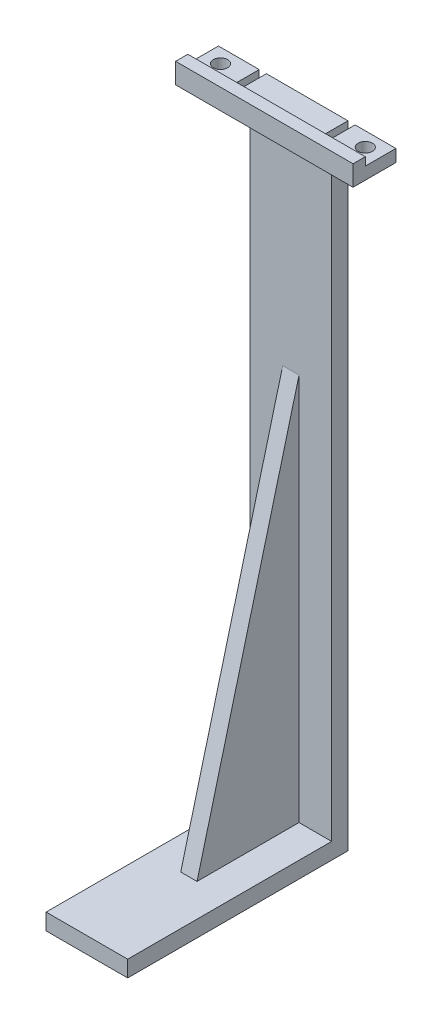
SolidWorks part; units mm, degrees
ref_plane "Front Plane" through (0, 0, 0) normal (0, 0, 1) x (1, 0, 0)
ref_plane "Top Plane" through (0, 0, 0) normal (0, 1, 0) x (1, 0, 0)
ref_plane "Right Plane" through (0, 0, 0) normal (1, 0, 0) x (0, 0, -1)
sketch "Sketch1" plane through (0, 0, 0) normal (0, 0, 1) x (1, 0, 0)
  line L1 (10, 77.5) -> (-10, 77.5)
  line L2 (10, 77.5) -> (10, -77.5)
  line L3 (10, -77.5) -> (-10, -77.5)
  line L4 (-10, 77.5) -> (-10, -77.5)
  line L5 (10, 77.5) -> (-10, -77.5) construction
  line L6 (10, -77.5) -> (-10, 77.5) construction
  point P0 (0, 0)
  dimension "D1" = 20
  dimension "D2" = 155
extrude "Boss-Extrude1" add sketch "Sketch1" along normal blind 4
sketch "Sketch2" plane through (0, 0, 4) normal (0, 0, 1) x (1, 0, 0)
  line L0 (10, -77.5) -> (10, 77.5) construction
  line L1 (-10, -77.5) -> (10, -77.5)
  line L2 (-10, -77.5) -> (-10, -73.5)
  line L3 (-10, -73.5) -> (10, -73.5)
  line L4 (10, -77.5) -> (10, -73.5)
  dimension "D1" = 4
extrude "Boss-Extrude3" add sketch "Sketch2" along normal blind 50 contours L3 L4 L1 L2
sketch "Sketch7" plane through (0, 0, 0) normal (1, 0, 0) x (0, 0, -1)
  line L0 (-29, -73.5) -> (-4, 21.5)
  line L1 (-54, -73.5) -> (-4, -73.5) construction
  line L2 (-4, -73.5) -> (-4, 77.5) construction
  dimension "D1" = 95
  dimension "D2" = 25
rib "Rib2" sketch "Sketch7" sketch "Sketch7" thickness 4 extrusion direction parallel to sketch draft on no parameters "D1"=4
sketch "Sketch8" plane through (0, 0, 4) normal (0, 0, 1) x (1, 0, 0)
  line L0 (-10, 77.5) -> (-10, -73.5) construction
  line L1 (10, 77.5) -> (-10, 77.5)
  line L2 (10, 77.5) -> (10, 74.5)
  line L3 (10, 74.5) -> (-10, 74.5)
  line L4 (-10, 77.5) -> (-10, 74.5)
  dimension "D1" = 3
extrude "Boss-Extrude4" add sketch "Sketch8" along normal blind 3.5
sketch "Sketch9" plane through (0, 0, 7.5) normal (0, 0, 1) x (1, 0, 0)
  line L0 (-21.75, 74.5) -> (0, 74.5)
  line L1 (-21.75, 79.5) -> (21.75, 79.5)
  line L2 (-21.75, 79.5) -> (-21.75, 74.5)
  line L4 (21.75, 79.5) -> (21.75, 74.5)
  line L5 (-10, 74.5) -> (10, 74.5) construction
  line L6 (0, 74.5) -> (21.75, 74.5)
  point P4 (0, 0)
  point P8 (5.8947, 74.5)
  point P9 (50.3542, 74.5)
  dimension "D1" = 43.5
  dimension "D3" = 5
extrude "Boss-Extrude6" add sketch "Sketch9" along normal blind 3
sketch "Sketch10" plane through (0, 0, 7.5) normal (0, 0, -1) x (-1, 0, 0)
  line L1 (21.75, 74.5) -> (11.75, 74.5)
  line L2 (21.75, 74.5) -> (21.75, 77.5)
  line L3 (21.75, 77.5) -> (11.75, 77.5)
  line L4 (11.75, 74.5) -> (11.75, 77.5)
  line L5 (-21.75, 74.5) -> (-11.75, 74.5)
  line L6 (-21.75, 74.5) -> (-21.75, 77.5)
  line L7 (-21.75, 77.5) -> (-11.75, 77.5)
  line L8 (-11.75, 74.5) -> (-11.75, 77.5)
  dimension "D1" = 10
  dimension "D2" = 3
  dimension "D3" = 10
  dimension "D4" = 3
extrude "Boss-Extrude7" add sketch "Sketch10" along normal blind 7.5
sketch "Sketch12" plane through (0, 77.5, 0) normal (0, 1, 0) x (1, 0, 0)
  line L1 (-21.75, -7.5) -> (-11.75, -7.5) construction
  line L2 (-21.75, 0) -> (-21.75, -7.5) construction
  line L3 (21.75, -7.5) -> (-21.75, -7.5) construction
  line L4 (21.75, 0) -> (21.75, -7.5) construction
  circle A0 centre (-17.75, -3.5) radius 1.75
  circle A1 centre (17.75, -3.5) radius 1.75
  dimension "D1" = 3.5
  dimension "D4" = 3.5
  dimension "D2" = 4
  dimension "D3" = 4
  dimension "D5" = 4
  dimension "D6" = 4
extrude "Cut-Extrude1" cut sketch "Sketch12" against normal blind 10
